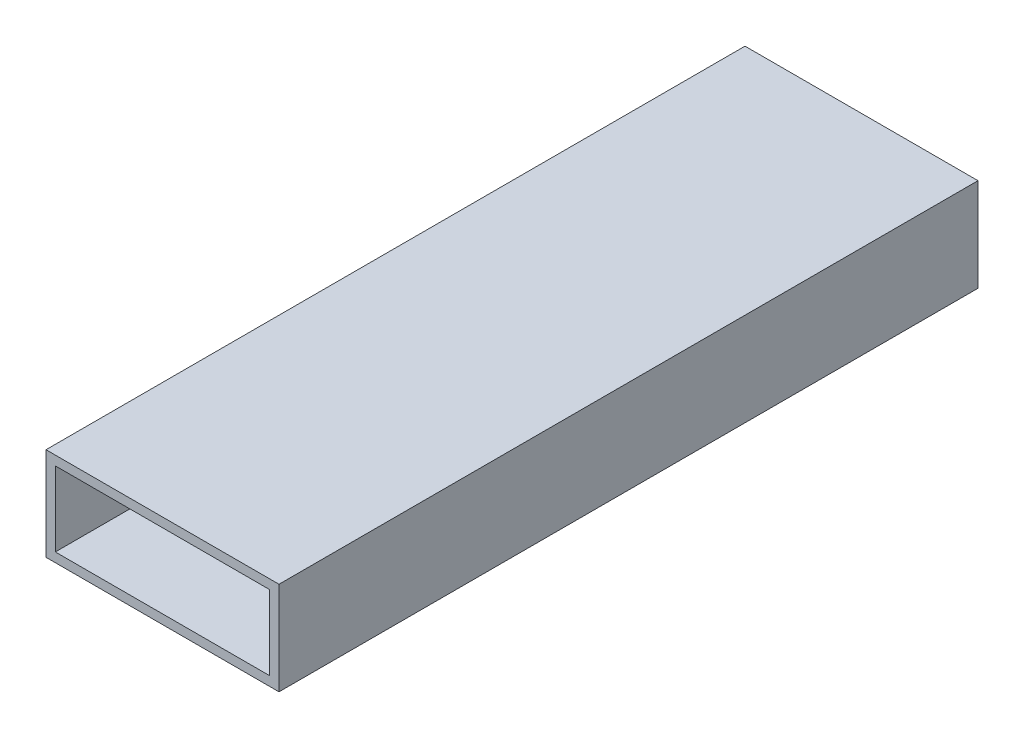
SolidWorks part; units mm, degrees
ref_plane "Přední rovina" through (0, 0, 0) normal (0, 0, 1) x (1, 0, 0)
ref_plane "Horní rovina" through (0, 0, 0) normal (0, 1, 0) x (1, 0, 0)
ref_plane "Pravá rovina" through (0, 0, 0) normal (1, 0, 0) x (0, 0, -1)
sketch "Skica1" plane through (0, 0, 0) normal (0, 0, 1) x (1, 0, 0)
  line L1 (0, 0) -> (50, 0)
  line L2 (0, 0) -> (0, 20)
  line L3 (0, 20) -> (50, 20)
  line L4 (50, 0) -> (50, 20)
  dimension "D1" = 50
  dimension "D2" = 20
extrude "Přidat vysunutím1" add sketch "Skica1" along normal blind 150
shell "Skořepina1" thickness 2
